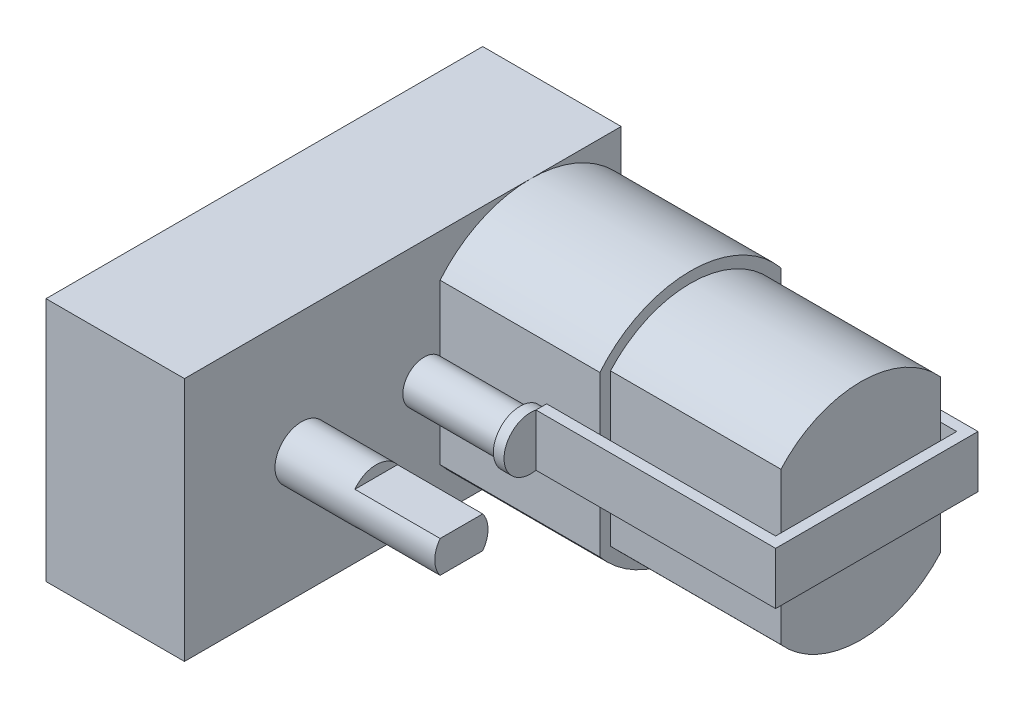
SolidWorks part; units mm, degrees
ref_plane "정면" through (0, 0, 0) normal (0, 0, 1) x (1, 0, 0)
ref_plane "윗면" through (0, 0, 0) normal (0, 1, 0) x (1, 0, 0)
ref_plane "우측면" through (0, 0, 0) normal (1, 0, 0) x (0, 0, -1)
sketch "스케치1" plane through (0, 0, 0) normal (1, 0, 0) x (0, 0, -1)
  line L1 (-20.5, -11.5) -> (20.5, -11.5)
  line L2 (-20.5, -11.5) -> (-20.5, 11.5)
  line L3 (-20.5, 11.5) -> (20.5, 11.5)
  line L4 (20.5, -11.5) -> (20.5, 11.5)
  line L5 (-20.5, -11.5) -> (20.5, 11.5) construction
  line L6 (-20.5, 11.5) -> (20.5, -11.5) construction
  point P0 (0, 0)
  dimension "D1" = 41
  dimension "D2" = 23
extrude "보스-돌출1" add sketch "스케치1" against normal blind 13
sketch "스케치2" plane through (0, 0, 0) normal (1, 0, 0) x (0, 0, -1)
  line L0 (-20.5, 11.5) -> (-20.5, -11.5) construction
  circle A0 centre (-9.5, 0) radius 2.5
  dimension "D1" = 5
  dimension "D2" = 11
extrude "보스-돌출2" add sketch "스케치2" along normal blind 15 and the other way blind 21
sketch "스케치3" plane through (-13, 0, 0) normal (-1, 0, 0) x (0, 0, 1)
  circle A0 centre (-2, 0) radius 2
  circle A3 centre (9.5, 0) radius 2.5
  circle A4 centre (9.5, 0) radius 2.5
  dimension "D1" = 4
  dimension "D3" = 11.5
  dimension "D2" = 0
extrude "보스-돌출3" add sketch "스케치3" along normal blind 2 and the other way blind 22
sketch "스케치5" plane through (-21, 0, 0) normal (-1, 0, 0) x (0, 0, 1)
  line L0 (7.5, 1.5) -> (11.5, 1.5)
  line L1 (0, 0) -> (20.5, 0) construction
  line L2 (20.5, 11.5) -> (20.5, -11.5) construction
  line L3 (7.5, -1.5) -> (11.5, -1.5)
  circle A0 centre (9.5, 0) radius 2.5 construction
  arc A1 (7.5, -1.5) -> (11.5, -1.5) centre (9.5, 0) ccw
  arc A2 (11.5, 1.5) -> (7.5, 1.5) centre (9.5, 0) ccw
  dimension "D1" = 1
extrude "컷-돌출1" cut sketch "스케치5" against normal offset from surface (7 mm away) 1 up to face at (-13, 0, 0)
sketch "스케치6" plane through (15, 0, 0) normal (1, 0, 0) x (0, 0, -1)
  line L0 (-11.5, 1.5) -> (-7.5, 1.5)
  line L1 (0, 0) -> (-20.5, 0) construction
  line L2 (-20.5, 11.5) -> (-20.5, -11.5) construction
  line L3 (-11.5, -1.5) -> (-7.5, -1.5)
  arc A0 (-11.5, -1.5) -> (-7.5, -1.5) centre (-9.5, 0) ccw
  arc A1 (-7.5, 1.5) -> (-11.5, 1.5) centre (-9.5, 0) ccw
  dimension "D1" = 1.5
  dimension "D2" = 5
extrude "컷-돌출2" cut sketch "스케치6" against normal offset from surface (8 mm away) 7 up to face at (0, 0, 0)
sketch "스케치7" plane through (0, 0, 0) normal (1, 0, 0) x (0, 0, -1)
  line L0 (3.5, 7.5) -> (3.5, -7.5)
  line L1 (20.5, 11.5) -> (-20.5, 11.5) construction
  line L3 (20.5, -11.5) -> (20.5, 11.5) construction
  line L4 (0, 0) -> (20.5, 0) construction
  line L5 (20.5, 7.5) -> (20.5, -7.5)
  arc A0 (3.5, 7.5) -> (20.5, 7.5) centre (12, 0.4688) cw
  arc A1 (3.5, -7.5) -> (20.5, -7.5) centre (12, -0.4688) ccw
  dimension "D2" = 15
  dimension "D1" = 17
extrude "보스-돌출4" add sketch "스케치7" along normal blind 15
sketch "스케치8" plane through (15, 0, 0) normal (1, 0, 0) x (0, 0, -1)
  line L4 (4.5, 7.1303) -> (4.5, -7.1303)
  line L5 (19.5, -7.1303) -> (19.5, 7.1303)
  line L6 (4.5, 7.1303) -> (4.5, -7.1303)
  line L7 (19.5, -7.1303) -> (19.5, 7.1303)
  arc A4 (19.5, 7.1303) -> (4.5, 7.1303) centre (12, 0.4688) ccw
  arc A5 (4.5, -7.1303) -> (19.5, -7.1303) centre (12, -0.4688) ccw
  arc A6 (19.5, 7.1303) -> (4.5, 7.1303) centre (12, 0.4688) ccw
  arc A7 (4.5, -7.1303) -> (19.5, -7.1303) centre (12, -0.4688) ccw
  dimension "D1" = 1
extrude "보스-돌출5" add sketch "스케치8" along normal blind 16
sketch "스케치10" plane through (0, 0, 0) normal (1, 0, 0) x (0, 0, -1)
  line L0 (2, 2) -> (3.5, 2)
  line L1 (3.5, 7.5) -> (3.5, -7.5) construction
  line L2 (2, -2) -> (3.5, -2)
  line L3 (3.5, 7.5) -> (3.5, 1.3229) construction
  line L4 (3.5, -2) -> (3.5, 2)
  line L5 (12, -11.5) -> (12, 11.5) construction
  line L6 (20.5, -2) -> (20.5, 2)
  line L7 (22, -2) -> (20.5, -2)
  line L8 (22, 2) -> (20.5, 2)
  circle A0 centre (2, 0) radius 2 construction
  arc A1 (3.5, -7.5) -> (20.5, -7.5) centre (12, -0.4688) ccw construction
  circle A2 centre (22, 0) radius 2
  dimension "D1" = 4
extrude "보스-돌출10" add sketch "스케치10" along normal up to surface (9 mm away) contours A2 L6 up to face at (9, 0, -1.75)
sketch "스케치11" plane through (9, 0, 0) normal (1, 0, 0) x (0, 0, -1)
  line L0 (12, 11.5) -> (12, -11.5) construction
  line L1 (20, -1.5) -> (20, 1.5)
  line L46 (4, -1.5) -> (4, 1.5)
  line L49 (4, -1.5) -> (4, 1.5)
  arc A0 (3.5, -7.5) -> (20.5, -7.5) centre (12, -0.4688) ccw construction
  arc A1 (20, 1.5) -> (20, -1.5) centre (22, 0) cw
  arc A28 (4, 1.5) -> (4, -1.5) centre (2, 0) ccw
  arc A29 (4, 1.5) -> (4, -1.5) centre (2, 0) ccw
  dimension "D1" = 0.5
extrude "보스-돌출7" add sketch "스케치11" along normal blind 1
sketch "스케치12" plane through (10, 0, 0) normal (1, 0, 0) x (0, 0, -1)
  line L0 (20.5, -7.5) -> (20.5, 7.5) construction
  line L1 (20.5, -2.4495) -> (21.5, -2.4495)
  line L2 (20.5, -2.4495) -> (20.5, 2.4495)
  line L3 (20.5, 2.4495) -> (21.5, 2.4495)
  line L4 (21.5, -2.4495) -> (21.5, 2.4495)
  line L5 (12, 11.5) -> (12, -11.5) construction
  line L6 (2.5, -2.4495) -> (2.5, 2.4495)
  line L7 (3.5, 2.4495) -> (2.5, 2.4495)
  line L8 (3.5, -2.4495) -> (3.5, 2.4495)
  line L9 (3.5, -2.4495) -> (2.5, -2.4495)
  arc A0 (20.5, -2) -> (20.5, 2) centre (22, 0) ccw construction
  arc A1 (20.5, 7.5) -> (3.5, 7.5) centre (12, 0.4688) ccw construction
  arc A2 (3.5, -7.5) -> (20.5, -7.5) centre (12, -0.4688) ccw construction
  dimension "D1" = 1
extrude "보스-돌출11" add sketch "스케치12" along normal offset from surface (21.5 mm away) 0.5 up to face at (31, 0, -12) offset beyond the face yes
sketch "스케치13" plane through (31.5, 0, 0) normal (1, 0, 0) x (0, 0, -1)
  line L1 (2.5, -2.4495) -> (21.5, -2.4495)
  line L2 (2.5, -2.4495) -> (2.5, 2.4495)
  line L3 (2.5, 2.4495) -> (21.5, 2.4495)
  line L4 (21.5, -2.4495) -> (21.5, 2.4495)
extrude "보스-돌출12" add sketch "스케치13" along normal blind 1
